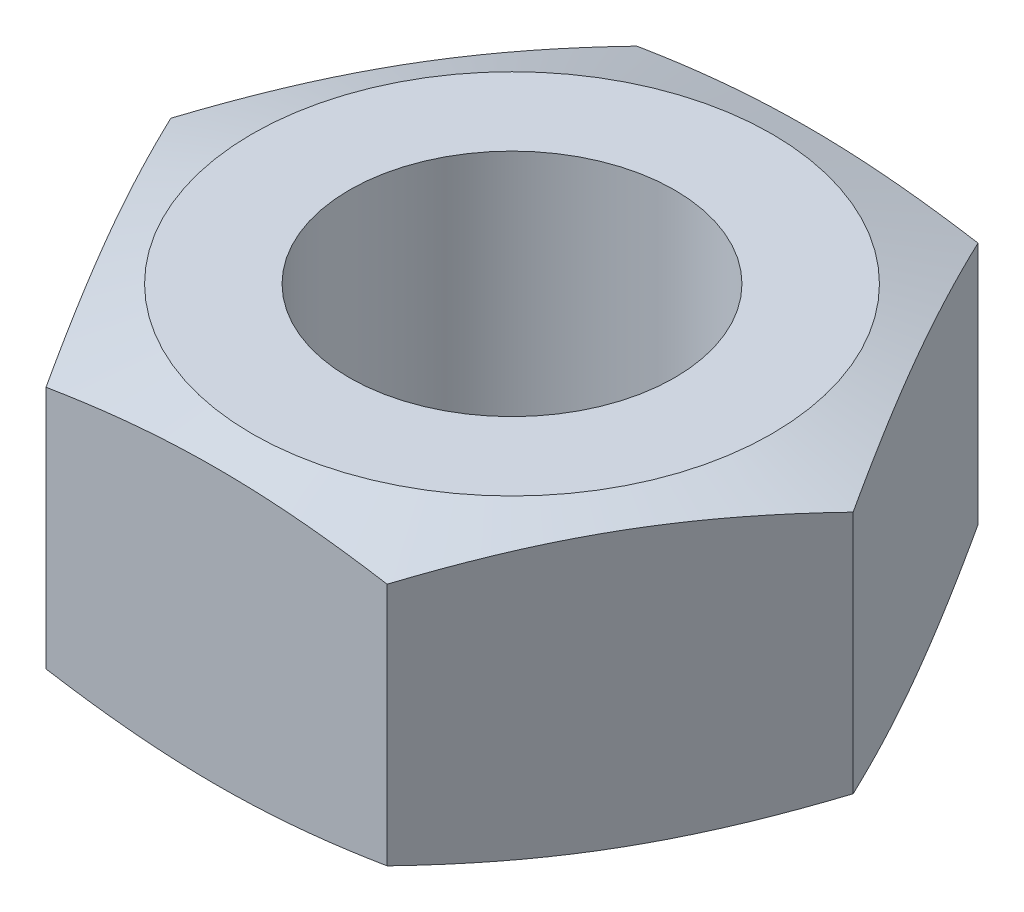
SolidWorks part; units mm, degrees
material "AISI 304"
ref_plane "前视基准面" through (0, 0, 0) normal (0, 0, 1) x (1, 0, 0)
ref_plane "上视基准面" through (0, 0, 0) normal (0, 1, 0) x (1, 0, 0)
ref_plane "右视基准面" through (0, 0, 0) normal (1, 0, 0) x (0, 0, -1)
sketch "草图1" plane through (0, 0, 0) normal (0, 1, 0) x (1, 0, 0)
  line L1 (12.5862, 0) -> (6.2931, 10.9)
  line L2 (6.2931, 10.9) -> (-6.2931, 10.9)
  line L3 (-6.2931, 10.9) -> (-12.5862, 0)
  line L4 (-12.5862, 0) -> (-6.2931, -10.9)
  line L5 (-6.2931, -10.9) -> (6.2931, -10.9)
  line L6 (6.2931, -10.9) -> (12.5862, 0)
  circle A0 centre (0, 0) radius 6
  circle A1 centre (0, 0) radius 10.9 construction
  dimension "D1" = 12
  dimension "D2" = 21.8
extrude "凸台-拉伸1" add sketch "草图1" along normal blind 11
cosmetic thread "装饰螺纹线1" parameters "D2"=14
sketch "草图2" plane through (0, 0, 0) normal (0, 0, 1) x (1, 0, 0)
  line L0 (0, 0) -> (0, 11) construction
  line L1 (-6.2931, 11) -> (6.2931, 11) construction
  line L2 (0, 11) -> (12.5862, 11) construction
  line L3 (0, 5.5) -> (14.9101, 5.5) construction
  line L4 (0, 0) -> (12.5862, 0) construction
  line L5 (9.5862, 11) -> (9.5862, 10) construction
  line L6 (9.5862, 10) -> (12.5862, 10) construction
  line L7 (12.5862, 11) -> (12.5862, 0) construction
  line L8 (12.5862, 10) -> (9.5862, 11)
  line L9 (9.5862, 1) -> (12.5862, 1) construction
  line L10 (9.5862, 0) -> (9.5862, 1) construction
  line L11 (12.5862, 1) -> (9.5862, 0)
  line L12 (9.5862, 11) -> (12.5862, 11)
  line L13 (12.5862, 11) -> (12.5862, 10)
  line L14 (12.5862, 1) -> (12.5862, 0)
  line L15 (12.5862, 0) -> (9.5862, 0)
  dimension "D1" = 1
  dimension "D2" = 3
revolve "切除-旋转3" cut sketch "草图2" angle 360 about L0
